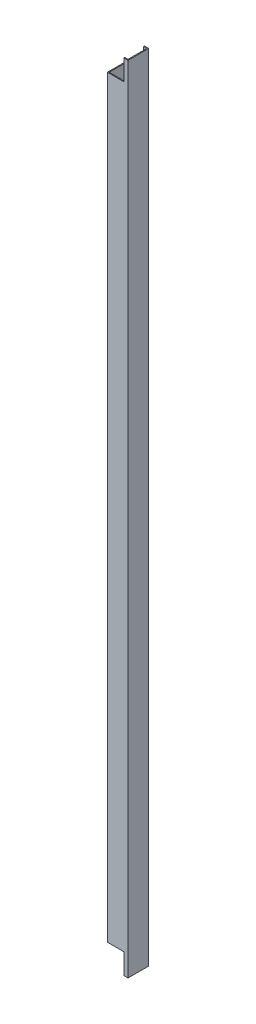
SolidWorks part; units mm, degrees
ref_plane "Front Plane" through (0, 0, 0) normal (0, 0, 1) x (1, 0, 0)
ref_plane "Top Plane" through (0, 0, 0) normal (0, 1, 0) x (1, 0, 0)
ref_plane "Right Plane" through (0, 0, 0) normal (1, 0, 0) x (0, 0, -1)
sketch "Sketch1" plane through (0, 0, 0) normal (0, 1, 0) x (1, 0, 0)
  line L0 (0, 0) -> (0, 50)
  line L1 (0, 50) -> (50, 50)
  line L2 (50, 50) -> (50, 0)
  line L3 (50, 0) -> (0, 0)
  line L4 (2.2, 47.8) -> (47.8, 47.8)
  line L5 (47.8, 47.8) -> (47.8, 2.2)
  line L6 (47.8, 2.2) -> (2.2, 2.2)
  line L7 (2.2, 2.2) -> (2.2, 47.8)
  dimension "D1" = 50
  dimension "D2" = 50
  dimension "D3" = 2.2
extrude "Boss-Extrude1" add sketch "Sketch1" along normal blind 1923
sketch "Sketch2" plane through (0, 0, 0) normal (0, 0, 1) x (1, 0, 0)
  line L0 (0, 0) -> (0, 50)
  line L1 (0, 1923) -> (0, 0) construction
  line L2 (0, 50) -> (40, 50)
  line L3 (40, 50) -> (40, 0)
  line L5 (40, 0) -> (0, 0)
  line L6 (0, 1923) -> (40, 1923)
  line L7 (0, 1923) -> (50, 1923) construction
  line L8 (40, 1923) -> (40, 1873)
  line L9 (40, 1873) -> (0, 1873)
  line L10 (0, 1873) -> (0, 1923)
  dimension "D1" = 50
  dimension "D2" = 40
  dimension "D3" = 50
  dimension "D4" = 40
extrude "Cut-Extrude2" cut sketch "Sketch2" against normal blind 50
equation "\"SquareTube_length\"=1923.0"
equation "\"D1@Boss-Extrude1\"=\"SquareTube_length\""
equation "\"SquareTube_inFront1_cutDepth50_R\"=0.5"
equation "\"D1@Sketch2\" = \"SquareTube_inFront8_cutDepth50_R\""
equation "\"SquareTube_inFront1_cutDepth50_L\"=0.5"
equation "\"D3@Sketch2\" = \"SquareTube_inFront8_cutDepth50_L\""
equation "\"CarBeamWidth\"=700.0"
equation "\"MetalSheet_3mm_length\"=5030.0"
equation "\"MetalSheet_3mm_width\"=1923.0"
equation "\"MetalSheet_3mm_FloorCut_L_length\"=1764.0"
equation "\"MetalSheet_3mm_FloorCut_L_disdance\"=1665.0"
equation "\"MetalSheet_3mm_FloorCut_R_length\"=1764.0"
equation "\"MetalSheet_3mm_FloorCut_R_disdance\"=1665.0"
equation "\"indoorHeight\"=1940.0"
equation "\"x\"=66.0"
equation "\"da\"=62.0"
equation "\"SquareTube_wheel_length\"= 750"
equation "\"channelSteel_length\"=5030.0"
equation "\"SquareTube_inFront2_cutDepth50_R\"=0.5"
equation "\"SquareTube_inFront2_cutDepth50_L\"=0.5"
equation "\"SquareTube_inFront3_cutDepth50_R\"=0.5"
equation "\"SquareTube_inFront3_cutDepth50_L\"=0.5"
equation "\"SquareTube_inFront4_cutDepth50_R\"=0.5"
equation "\"SquareTube_inFront4_cutDepth50_L\"=0.5"
equation "\"SquareTube_inFront5_cutDepth50_R\"=50"
equation "\"SquareTube_inFront5_cutDepth50_L\"=50"
equation "\"SquareTube_inFront6_cutDepth50_R\"=50"
equation "\"SquareTube_inFront6_cutDepth50_L\"=50"
equation "\"SquareTube_inFront7_cutDepth50_R\"=50"
equation "\"SquareTube_inFront7_cutDepth50_L\"=50"
equation "\"SquareTube_inFront8_cutDepth50_R\"=50"
equation "\"SquareTube_inFront8_cutDepth50_L\"=50"
equation "\"SquareTube_inFront9_cutDepth50_R\"=50"
equation "\"SquareTube_inFront9_cutDepth50_L\"=50"
equation "\"SquareTube_inFront10_cutDepth50_R\"=50"
equation "\"SquareTube_inFront10_cutDepth50_L\"=50"
equation "\"SquareTube_inBack1_cutDepth50_R\"=50"
equation "\"SquareTube_inBack1_cutDepth50_L\"=50"
equation "\"SquareTube_inBack2_cutDepth50_R\"=50"
equation "\"SquareTube_inBack2_cutDepth50_L\"=50"
equation "\"SquareTube_inBack3_cutDepth50_R\"=50"
equation "\"SquareTube_inBack3_cutDepth50_L\"=50"
equation "\"SquareTube_inBack4_cutDepth50_R\"=50"
equation "\"SquareTube_inBack4_cutDepth50_L\"=50"
equation "\"SquareTube_inBack5_cutDepth50_R\"=50"
equation "\"SquareTube_inBack5_cutDepth50_L\"=50"
equation "\"SquareTube_inBack6_cutDepth50_R\"=0.5"
equation "\"SquareTube_inBack6_cutDepth50_L\"=0.5"
